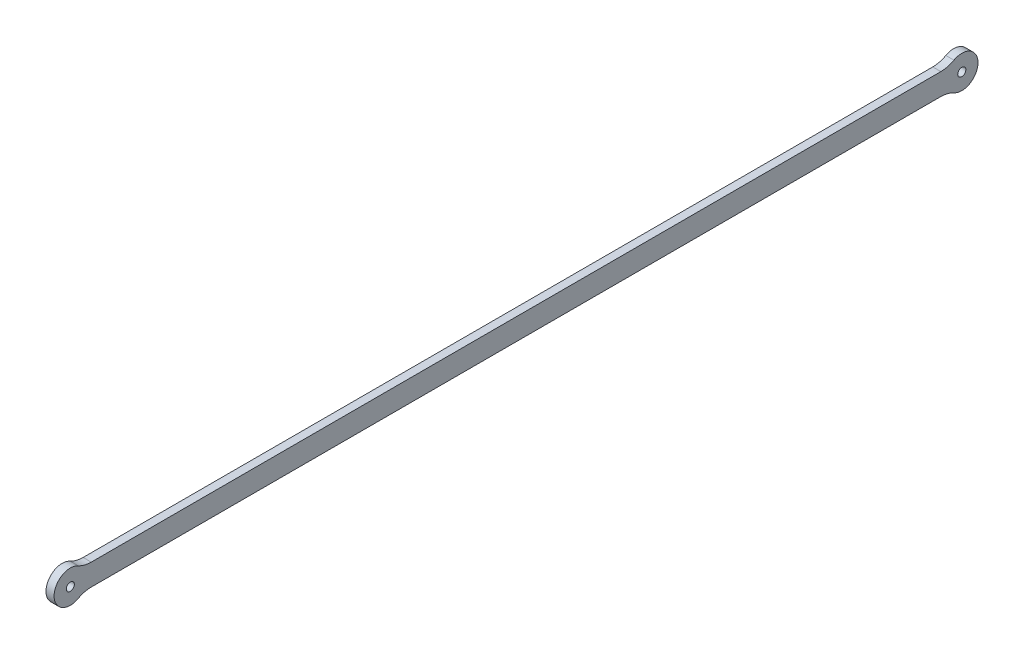
SolidWorks part; units mm, degrees
material "Hexcel AS4C (3000 Filaments)"
ref_plane "Front Plane" through (0, 0, 0) normal (0, 0, 1) x (1, 0, 0)
ref_plane "Top Plane" through (0, 0, 0) normal (0, 1, 0) x (1, 0, 0)
ref_plane "Right Plane" through (0, 0, 0) normal (1, 0, 0) x (0, 0, -1)
sketch "Sketch1" plane through (0, 0, 0) normal (1, 0, 0) x (0, 0, -1)
  line L0 (0, 0) -> (0, 4)
  line L1 (0, 0) -> (165, 0)
  line L2 (0, 4) -> (160.5279, 4)
  line L7 (80.2639, 4) -> (80.2639, 0)
  line L8 (160.5279, -4) -> (0, -4)
  line L9 (160.5279, -4) -> (160.5279, 4)
  line L10 (0, -4) -> (0, 4)
  line L11 (160.5279, 4) -> (0, 4)
  line L12 (160.5279, -4) -> (0, 4) construction
  line L13 (0, -4) -> (160.5279, 4) construction
  circle A0 centre (165, 0) radius 1.5
  circle A2 centre (165, 0) radius 6
  dimension "D3" = 3
  dimension "D4" = 12
  dimension "D1" = 4
  dimension "D2" = 165
extrude "Boss-Extrude1" add sketch "Sketch1" along normal blind 3
mirror "Mirror1" about plane through (0, 0, 0) normal (0, 0, 1) of "Boss-Extrude1"
fillet "Fillet1" radius 10 1 edges at (1.5, 4, 160.5279)
fillet "Fillet2" radius 10 1 edges at (1.5, -4, 160.5279)
fillet "Fillet3" radius 10 1 edges at (1.5, -4, -160.5279)
fillet "Fillet4" radius 10 1 edges at (1.5, 4, -160.5279)
